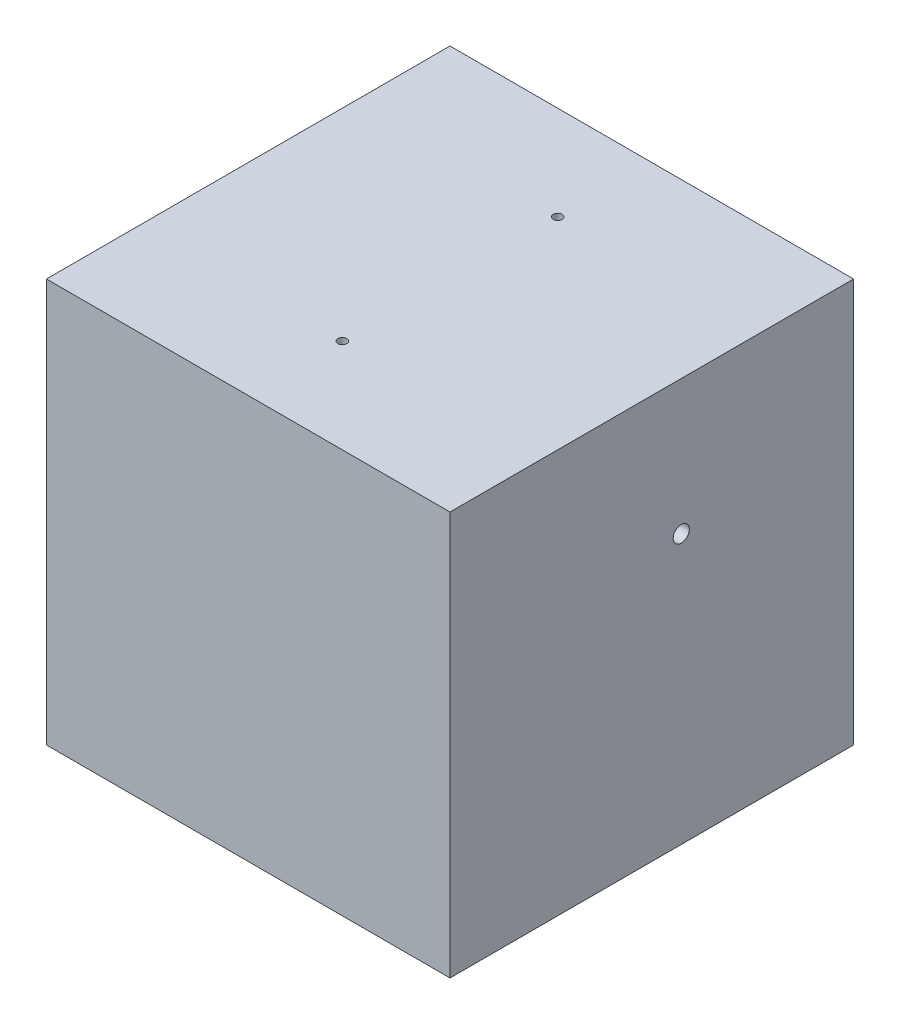
SolidWorks part; units mm, degrees
ref_plane "前视基准面" through (0, 0, 0) normal (0, 0, 1) x (1, 0, 0)
ref_plane "上视基准面" through (0, 0, 0) normal (0, 1, 0) x (1, 0, 0)
ref_plane "右视基准面" through (0, 0, 0) normal (1, 0, 0) x (0, 0, -1)
sketch "草图1" plane through (0, 0, 0) normal (0, 1, 0) x (1, 0, 0)
  line L1 (0, 0) -> (150, 0)
  line L2 (0, 0) -> (0, 150)
  line L3 (0, 150) -> (150, 150)
  line L4 (150, 0) -> (150, 150)
  dimension "D1" = 150
  dimension "D2" = 150
extrude "凸台-拉伸1" add sketch "草图1" along normal blind 5
sketch "草图3" plane through (0, 0, 0) normal (0, -1, 0) x (1, 0, 0)
  line L0 (0, -75) -> (150, -75) construction
  line L1 (0, -150) -> (0, 0) construction
  line L2 (150, 0) -> (150, -150) construction
  line L3 (0, 0) -> (150, 0) construction
  line L4 (0, -150) -> (150, -150)
  line L5 (0, -150) -> (0, 0)
  line L6 (0, 0) -> (150, 0)
  line L7 (150, -150) -> (150, 0)
  line L8 (0, -150) -> (150, 0) construction
  line L9 (0, 0) -> (150, -150) construction
  line L11 (5, -5) -> (145, -5)
  line L12 (5, -5) -> (5, -145)
  line L13 (5, -145) -> (145, -145)
  line L14 (145, -5) -> (145, -145)
  line L15 (5, -5) -> (145, -145) construction
  line L16 (5, -145) -> (145, -5) construction
  point P6 (75, -75)
  point P13 (75, -75)
  dimension "D1" = 140
extrude "凸台-拉伸2" add sketch "草图3" along normal blind 140
sketch "草图5" plane through (0, 5, 0) normal (0, 1, 0) x (1, 0, 0)
  line L0 (0, 75) -> (150, 75) construction
  line L1 (0, 150) -> (0, 0) construction
  line L2 (150, 0) -> (150, 150) construction
  line L3 (75, 75) -> (75, 150) construction
  line L4 (150, 150) -> (0, 150) construction
  circle A0 centre (75, 115) radius 1.65
  circle A1 centre (75, 35) radius 1.65
  dimension "D1" = 3.3
  dimension "D2" = 40
extrude "切除-拉伸1" cut sketch "草图5" against normal blind 5
sketch "草图7" plane through (150, 0, 0) normal (1, 0, 0) x (0, 0, -1)
  line L1 (0, 5) -> (0, -140) construction
  line L4 (0, 5) -> (150, 5) construction
  circle A0 centre (85.95, -45) radius 3
  dimension "D2" = 6
  dimension "D1" = 85.95
  dimension "D3" = 50
sketch "草图8" plane through (0, -140, 0) normal (0, -1, 0) x (1, 0, 0)
  line L0 (0, -75) -> (150, -75) construction
  line L1 (0, 0) -> (150, 0)
  line L2 (0, 0) -> (0, -150)
  line L3 (0, -150) -> (150, -150)
  line L4 (150, 0) -> (150, -150)
  circle A0 centre (75, -75) radius 50
  dimension "D1" = 100
extrude "凸台-拉伸3" add sketch "草图8" along normal blind 5
extrude "切除-拉伸2" cut sketch "草图7" against normal through all
